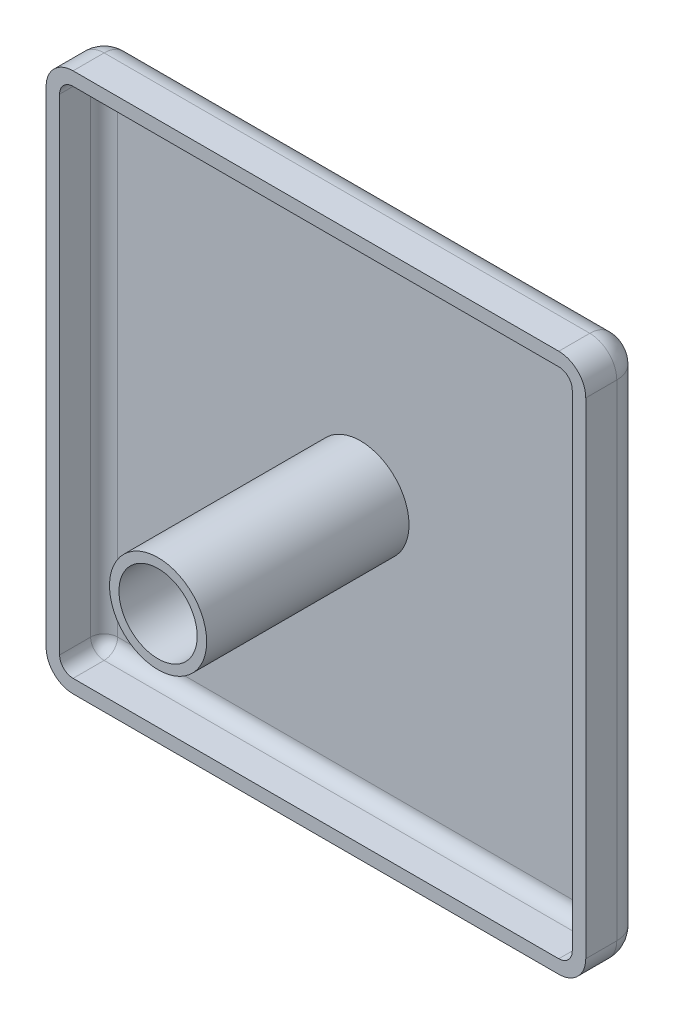
SolidWorks part; units mm, degrees
ref_plane "前视基准面" through (0, 0, 0) normal (0, 0, 1) x (1, 0, 0)
ref_plane "上视基准面" through (0, 0, 0) normal (0, 1, 0) x (1, 0, 0)
ref_plane "右视基准面" through (0, 0, 0) normal (1, 0, 0) x (0, 0, -1)
sketch "草图1" plane through (0, 0, 0) normal (0, 0, 1) x (1, 0, 0)
  line L1 (-20, 20) -> (20, 20)
  line L2 (-20, 20) -> (-20, -20)
  line L3 (-20, -20) -> (20, -20)
  line L4 (20, 20) -> (20, -20)
  line L5 (-20, 20) -> (20, -20) construction
  line L6 (-20, -20) -> (20, 20) construction
  point P0 (0, 0)
  dimension "D1" = 40
  dimension "D2" = 40
extrude "凸台-拉伸1" add sketch "草图1" along normal blind 4.3
fillet "圆角1" radius 2 8 edges at (0, 20, 0) (-20, 0, 0) (0, -20, 0) (20, 0, 0) (-20, -20, 2.15) (20, -20, 2.15) (20, 20, 2.15) (-20, 20, 2.15)
shell "抽壳1" thickness 1
sketch "草图2" plane through (0, 0, 1) normal (0, 0, 1) x (1, 0, 0)
  circle A0 centre (0, 0) radius 3.6
  dimension "D1" = 7.2
extrude "凸台-拉伸2" add sketch "草图2" along normal blind 15
sketch "草图3" plane through (0, 0, 16) normal (0, 0, 1) x (1, 0, 0)
  circle A1 centre (0, 0) radius 2.9
extrude "切除-拉伸1" cut sketch "草图3" against normal up to surface (15 mm away) up to face at (0, 0, 1)
